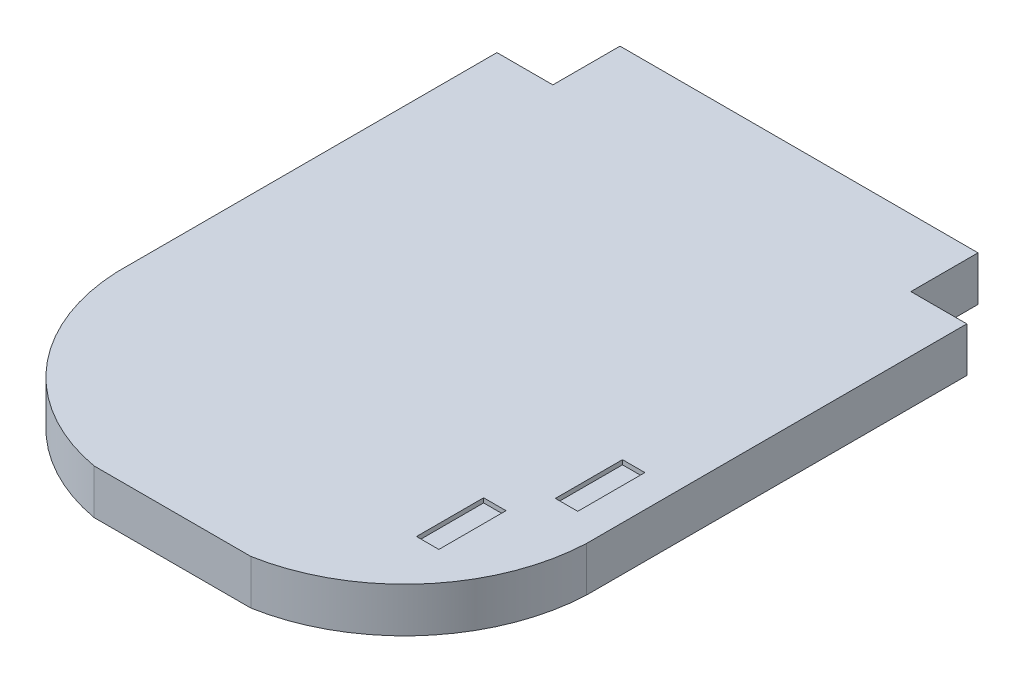
SolidWorks part; units mm, degrees
ref_plane "前视基准面" through (0, 0, 0) normal (0, 0, 1) x (1, 0, 0)
ref_plane "上视基准面" through (0, 0, 0) normal (0, 1, 0) x (1, 0, 0)
ref_plane "右视基准面" through (0, 0, 0) normal (1, 0, 0) x (0, 0, -1)
other "Configuration Table"
sketch "草图1" plane through (0, 0, 0) normal (0, 1, 0) x (1, 0, 0)
  line L0 (0, 14) -> (0, 0) construction
  line L1 (-8, 14) -> (8, 14)
  line L2 (-10.5, 11) -> (-10.5, -6)
  line L4 (10.5, 11) -> (10.5, -6)
  line L8 (-8, 14) -> (-8, 11)
  line L9 (-8, 11) -> (-10.5, 11)
  line L12 (8, 14) -> (8, 11)
  line L13 (8, 11) -> (10.5, 11)
  line L17 (-3.5, -14) -> (3.5, -14)
  arc A0 (-10.5, -6) -> (-3.5, -14) centre (-2, -5.625) ccw
  arc A2 (10.5, -6) -> (3.5, -14) centre (2, -5.625) cw
  point P0 (0, 0)
  point P4 (-2.5, -14)
  point P9 (-10.5, -6)
  point P16 (-2.5, -14)
  point P17 (-2.5, -14)
  point P20 (-4.6074, -14)
  point P21 (-3.7966, -13.8942)
  point P22 (-3.5, -14)
  point P23 (-10.5, -5.7364)
  point P24 (2.6675, -14)
  dimension "D3" = 28
  dimension "D10" = 4
  dimension "D1" = 3
  dimension "D2" = 21
  dimension "D4" = 2.5
  dimension "D5" = 3
  dimension "D6" = 2.5
  dimension "D7" = 14
  dimension "D8" = 7
  dimension "D9" = 17
extrude "凸台-拉伸1" add sketch "草图1" along normal blind 2
sketch "草图2" plane through (0, 2, 0) normal (0, 1, 0) x (1, 0, 0)
  line L1 (8.0614, -1.9497) -> (9.0614, -1.9497)
  line L2 (8.0614, -1.9497) -> (8.0614, -4.9497)
  line L3 (8.0614, -4.9497) -> (9.0614, -4.9497)
  line L4 (9.0614, -1.9497) -> (9.0614, -4.9497)
  line L5 (6.4331, -6.5276) -> (7.4331, -6.5276)
  line L6 (6.4331, -6.5276) -> (6.4331, -9.5276)
  line L7 (6.4331, -9.5276) -> (7.4331, -9.5276)
  line L8 (7.4331, -6.5276) -> (7.4331, -9.5276)
  dimension "D1" = 1
  dimension "D2" = 3
extrude "切除-拉伸1" cut sketch "草图2" against normal blind 0.2
